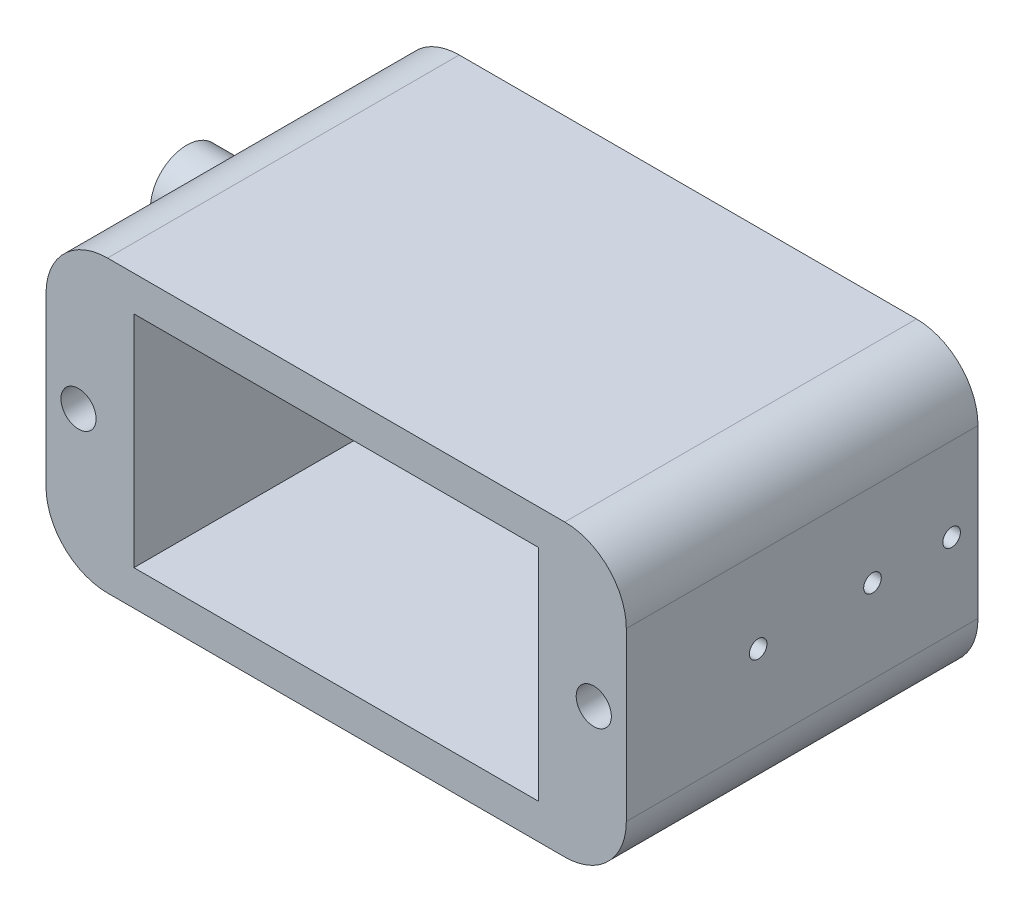
SolidWorks part; units mm, degrees
ref_plane "Front Plane" through (0, 0, 0) normal (0, 0, 1) x (1, 0, 0)
ref_plane "Top Plane" through (0, 0, 0) normal (0, 1, 0) x (1, 0, 0)
ref_plane "Right Plane" through (0, 0, 0) normal (1, 0, 0) x (0, 0, -1)
sketch "Sketch1" plane through (0, 0, 0) normal (0, 0, 1) x (1, 0, 0)
  line L1 (-11.5, -6.25) -> (11.5, -6.25)
  line L2 (-11.5, -6.25) -> (-11.5, 6.25)
  line L3 (-11.5, 6.25) -> (11.5, 6.25)
  line L4 (11.5, -6.25) -> (11.5, 6.25)
  line L5 (-11.5, -6.25) -> (11.5, 6.25) construction
  line L6 (-11.5, 6.25) -> (11.5, -6.25) construction
  line L7 (-16.5, -8.25) -> (16.5, -8.25)
  line L8 (-16.5, -8.25) -> (-16.5, 8.25)
  line L9 (-16.5, 8.25) -> (16.5, 8.25)
  line L10 (16.5, -8.25) -> (16.5, 8.25)
  line L11 (-16.5, -8.25) -> (16.5, 8.25) construction
  line L12 (-16.5, 8.25) -> (16.5, -8.25) construction
  point P0 (0, 0)
  point P6 (0, 0)
  dimension "D1" = 12.5
  dimension "D2" = 23
  dimension "D3" = 33
  dimension "D4" = 16.5
extrude "Boss-Extrude1" add sketch "Sketch1" along normal blind 16
sketch "Sketch2" plane through (0, 0, 16) normal (0, 0, 1) x (1, 0, 0)
  line L0 (-16.5, 0) -> (16.5, 0) construction
  line L1 (-16.5, 8.25) -> (-16.5, -8.25) construction
  line L2 (16.5, -8.25) -> (16.5, 8.25) construction
  line L3 (0, 8.25) -> (0, -8.25) construction
  line L4 (16.5, 8.25) -> (-16.5, 8.25) construction
  line L5 (-16.5, -8.25) -> (16.5, -8.25) construction
  circle A0 centre (-14.65, 0) radius 1
  circle A1 centre (14.65, 0) radius 1
  dimension "D1" = 2
  dimension "D2" = 1.85
extrude "Cut-Extrude1" cut sketch "Sketch2" against normal blind 4
sketch "Sketch6" plane through (0, 0, 0) normal (0, 0, -1) x (-1, 0, 0)
  line L0 (-16.5, 0) -> (16.5, 0) construction
  line L1 (-16.5, -8.25) -> (-16.5, 8.25) construction
  line L2 (16.5, 8.25) -> (16.5, -8.25) construction
  line L3 (0, 8.25) -> (0, -8.25) construction
  line L4 (-16.5, 8.25) -> (16.5, 8.25) construction
  line L5 (16.5, -8.25) -> (-16.5, -8.25) construction
  line L6 (-11.5, -6.25) -> (-11.5, 6.25) construction
  line L8 (-11.5, 8.25) -> (16.5, 8.25)
  line L10 (-11.5, -8.25) -> (16.5, -8.25)
  line L11 (16.5, 8.25) -> (16.5, -8.25)
  line L12 (-11.5, -8.25) -> (-16.5, -8.25)
  line L13 (-16.5, -8.25) -> (-16.5, 8.25)
  line L14 (-16.5, 8.25) -> (-11.5, 8.25)
  circle A0 centre (-5.175, 0) radius 4.575
  dimension "D1" = 6.325
  dimension "D2" = 9.15
extrude "Boss-Extrude5" add sketch "Sketch6" along normal blind 4
sketch "Sketch7" plane through (0, 0, -4) normal (0, 0, -1) x (-1, 0, 0)
  line L0 (-16.5, 0) -> (16.5, 0) construction
  line L1 (-14.5, 5) -> (-11.5, 5)
  line L2 (-14.5, 5) -> (-14.5, -5)
  line L3 (-14.5, -5) -> (-11.5, -5)
  line L4 (-11.5, 5) -> (-11.5, -5)
  line L5 (-16.5, 8.25) -> (-16.5, -8.25) construction
  line L6 (16.5, -8.25) -> (16.5, 8.25) construction
  dimension "D1" = 10
  dimension "D2" = 5
  dimension "D3" = 3
  dimension "D4" = 5
extrude "Cut-Extrude3" cut sketch "Sketch7" against normal blind 11
sketch "Sketch9" plane through (16.5, 0, 0) normal (1, 0, 0) x (0, 0, -1)
  line L0 (-16, 0) -> (4, 0) construction
  line L1 (-16, -8.25) -> (-16, 8.25) construction
  line L2 (4, 8.25) -> (4, -8.25) construction
  circle A0 centre (-2, 0) radius 0.5
  circle A1 centre (2.5, 0) radius 0.5
  circle A2 centre (-8.5, 0) radius 0.5
  dimension "D1" = 1
  dimension "D2" = 1
  dimension "D3" = 14
  dimension "D4" = 4.5
  dimension "D6" = 1
  dimension "D7" = 6.5
extrude "Cut-Extrude4" cut sketch "Sketch9" against normal blind 4
sketch "Sketch10" plane through (-16.5, 0, 0) normal (-1, 0, 0) x (0, 0, 1)
  line L0 (-4, 0) -> (16, 0) construction
  line L1 (-4, -8.25) -> (-4, 8.25) construction
  line L2 (16, 8.25) -> (16, -8.25) construction
  circle A0 centre (2, 0) radius 2.06
  dimension "D1" = 4.12
  dimension "D2" = 14
extrude "Boss-Extrude6" add sketch "Sketch10" along normal blind 6
fillet "Fillet1" radius 3.5 4 edges at (16.5, 8.25, 6) (-16.5, 8.25, 6) (-16.5, -8.25, 6) (16.5, -8.25, 6)
